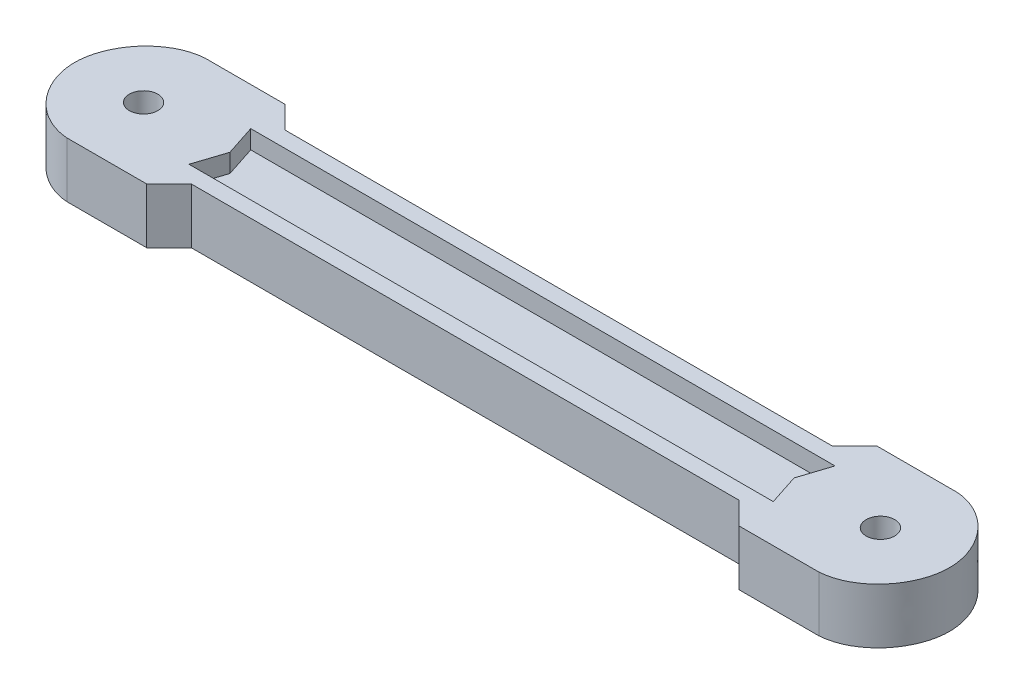
SolidWorks part; units mm, degrees
ref_plane "Plan de face" through (0, 0, 0) normal (0, 0, 1) x (1, 0, 0)
ref_plane "Plan de dessus" through (0, 0, 0) normal (0, 1, 0) x (1, 0, 0)
ref_plane "Plan de droite" through (0, 0, 0) normal (1, 0, 0) x (0, 0, -1)
sketch "Esquisse1" plane through (0, 0, 0) normal (0, 1, 0) x (1, 0, 0)
  line L0 (-47.5, -7.5) -> (-47.5, 7.5)
  line L1 (-3.3, 0) -> (3.3, 0) construction
  line L2 (-47.5, 7.5) -> (47.5, 7.5)
  line L3 (0, -3.3) -> (0, 3.3) construction
  line L4 (-47.5, -7.5) -> (47.5, -7.5)
  line L5 (47.5, -7.5) -> (47.5, 7.5)
  point P5 (-47.5, 0)
  point P6 (47.5, 0)
  point P10 (0, -7.5)
  point P11 (0, 7.5)
  dimension "D1" = 15
  dimension "D2" = 95
extrude "Boss.-Extru.1" add sketch "Esquisse1" along normal blind 6
sketch "Esquisse2" plane through (0, 0, 0) normal (0, -1, 0) x (1, 0, 0)
  line L0 (3.3, 0) -> (-3.3, 0) construction
  line L1 (0, -3.3) -> (0, 3.3) construction
  line L2 (-47.5, -7.5) -> (-47.5, 7.5) construction
  circle A0 centre (-40, 0) radius 7.5 construction
  circle A1 centre (40, 0) radius 7.5 construction
  dimension "D1" = 7.5
  dimension "D2" = 15
sketch "Esquisse3" plane through (0, 0, 0) normal (0, -1, 0) x (1, 0, 0)
  line L0 (-47.5, -7.5) -> (-47.5, 7.5) construction
  line L1 (0, -3.3) -> (0, 3.3) construction
  circle A0 centre (-40, 0) radius 1.55
  circle A1 centre (40, 0) radius 1.55
  dimension "D1" = 3.1
  dimension "D2" = 7.5
sketch "Esquisse4" plane through (0, 6, 0) normal (0, 1, 0) x (1, 0, 0)
  line L0 (-32.1592, 7.5) -> (-29.7385, 5.0794)
  line L1 (47.5, 7.5) -> (-47.5, 7.5) construction
  line L2 (-29.7385, 5.0794) -> (29.7385, 5.0794)
  line L3 (0, -3.3) -> (0, 3.3) construction
  line L4 (-32.1592, 7.5) -> (-40, 7.5)
  line L5 (-3.3, 0) -> (3.3, 0) construction
  line L6 (-47.5, 7.5) -> (-47.5, -7.5) construction
  line L7 (32.1592, 7.5) -> (40, 7.5)
  line L8 (32.1592, 7.5) -> (29.7385, 5.0794)
  line L9 (32.1592, -7.5) -> (29.7385, -5.0794)
  line L10 (32.1592, -7.5) -> (40, -7.5)
  line L11 (-32.1592, -7.5) -> (-40, -7.5)
  line L12 (-29.7385, -5.0794) -> (29.7385, -5.0794)
  line L13 (-32.1592, -7.5) -> (-29.7385, -5.0794)
  line L15 (-55.3206, 15) -> (55.3206, 15)
  line L16 (-55.3206, 15) -> (-55.3206, -15)
  line L17 (-55.3206, -15) -> (55.3206, -15)
  line L18 (55.3206, 15) -> (55.3206, -15)
  line L19 (-55.3206, 15) -> (55.3206, -15) construction
  line L20 (-55.3206, -15) -> (55.3206, 15) construction
  circle A0 centre (-40, 0) radius 7.5 construction
  spline S0 degree 3 poles (-40, 7.5) (-44.0852, 7.774) (-50.9148, 0) (-44.0852, -7.774) (-40, -7.5) knots 0 0 0 0 0.5 1 1 1 1
  spline S1 degree 3 poles (40, 7.5) (44.0852, 7.774) (50.9148, 0) (44.0852, -7.774) (40, -7.5) knots 0 0 0 0 0.5 1 1 1 1
  point P28 (0, 5.0794)
  point P42 (0, -5.0794)
  point P43 (0, 0)
  dimension "D1" = 17.7615
  dimension "D4" = 15.3206
  dimension "D2" = 15.3408
  dimension "D3" = 15.3206
  dimension "D5" = 30
  dimension "D6" = 7.5
  dimension "D7" = 7.5
  dimension "D8" = 7.5
  dimension "D9" = 7.5
  dimension "D10" = 7.5
  dimension "D11" = 1.9098
  dimension "D12" = 2.5
extrude "Enlèv. mat.-Extru.1" cut sketch "Esquisse4" against normal blind 12
extrude "Enlèv. mat.-Extru.2" cut sketch "Esquisse3" against normal blind 12
sketch "Esquisse5" plane through (0, 6, 0) normal (0, 1, 0) x (1, 0, 0)
  line L0 (-30.625, 0) -> (-31.7174, 3.3519)
  line L1 (-3.3, 0) -> (3.3, 0) construction
  line L2 (-31.7174, 3.3519) -> (31.7174, 3.3519)
  line L3 (0, -3.3) -> (0, 3.3) construction
  line L4 (-31.7174, -3.3519) -> (31.7174, -3.3519)
  line L5 (-30.625, 0) -> (-31.7174, -3.3519)
  line L6 (30.625, 0) -> (31.7174, -3.3519)
  line L7 (30.625, 0) -> (31.7174, 3.3519)
  line L8 (-29.7385, 5.0794) -> (29.7385, 5.0794) construction
  point P12 (0, -3.3519)
  point P13 (0, 3.3519)
  dimension "D1" = 8.2826
  dimension "D2" = 1.9789
  dimension "D3" = 9.375
  dimension "D4" = 1.7274
extrude "Enlèv. mat.-Extru.3" cut sketch "Esquisse5" against normal blind 2
